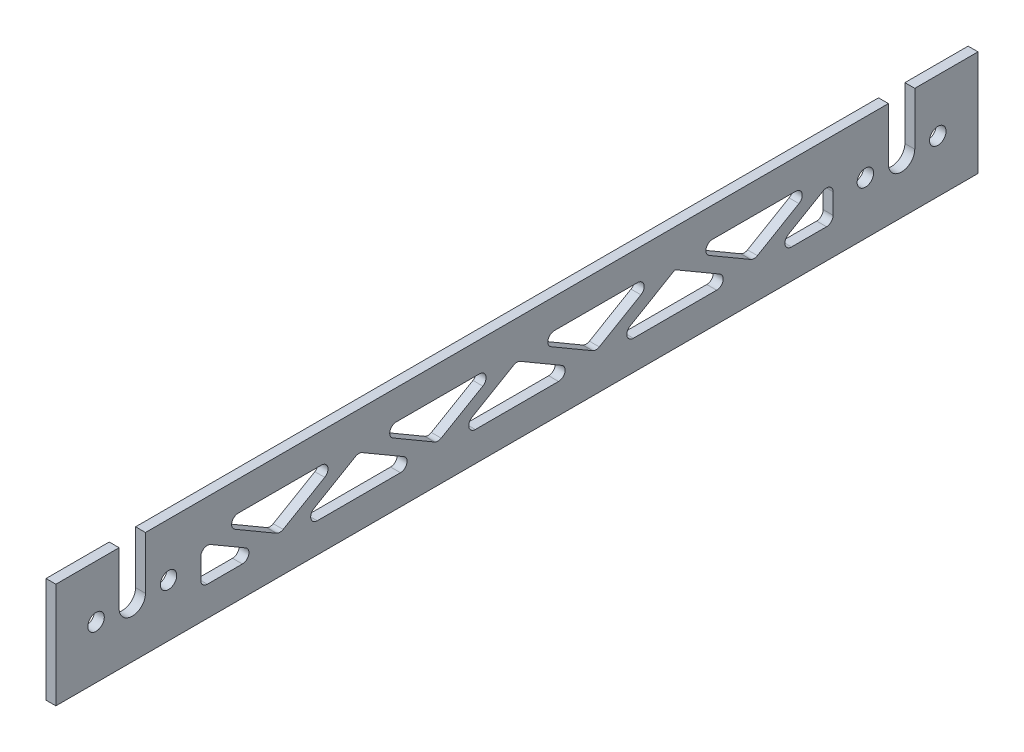
SolidWorks part; units mm, degrees
material "Thornel Mat VMA"
ref_plane "Front Plane" through (0, 0, 0) normal (0, 0, 1) x (1, 0, 0)
ref_plane "Top Plane" through (0, 0, 0) normal (0, 1, 0) x (1, 0, 0)
ref_plane "Right Plane" through (0, 0, 0) normal (1, 0, 0) x (0, 0, -1)
sketch "Sketch1" plane through (0, 0, 0) normal (1, 0, 0) x (0, 0, -1)
  line L0 (0, 0) -> (0, 75.5)
  line L2 (21.5, 75.5) -> (40, 0)
  line L3 (40, 0) -> (35.8817, 0)
  line L4 (35.8817, 0) -> (29.7558, 25)
  line L5 (29.7558, 25) -> (4, 25)
  line L6 (4, 25) -> (4, 0)
  line L7 (4, 0) -> (0, 0)
  line L8 (4, 69.5) -> (18.8519, 69.5)
  line L9 (18.8519, 69.5) -> (4, 29)
  line L10 (4, 29) -> (4, 69.5)
  line L11 (8.2605, 29) -> (20.5584, 62.5355)
  line L12 (20.5584, 62.5355) -> (28.7757, 29)
  line L13 (28.7757, 29) -> (8.2605, 29)
  line L15 (21.5, 75.5) -> (0, 75.5)
  circle A0 centre (5.5, 72.5) radius 1.05
  circle A1 centre (18.5, 72.5) radius 1.05
  dimension "D4" = 2.1
  dimension "D1" = 4
  dimension "D2" = 4
  dimension "D3" = 25
  dimension "D5" = 72.5
  dimension "D6" = 40
  dimension "D8" = 13
  dimension "D9" = 5.5
  dimension "D10" = 3
  dimension "D11" = 4
  dimension "D12" = 3
  dimension "D13" = 4
  dimension "D7" = 3
extrude "Boss-Extrude1" add sketch "Sketch1" along normal blind 1.5
fillet "Fillet1" radius 1.5 9 edges at (0.75, 29, -4) (0.75, 29, -8.2605) (0.75, 25, -29.7558) (0.75, 25, -4) (0.75, 69.5, -4) (0.75, 69.5, -18.8519) (0.75, 62.5355, -20.5584) (0.75, 29, -28.7757) (0.75, 75.5, -21.5)
sketch "Sketch2" plane through (1.5, 0, 0) normal (1, 0, 0) x (0, 0, -1)
  line L0 (70, 16) -> (70, 0) construction
  line L3 (0, 16) -> (103.9205, 16)
  line L14 (109.9641, 23.857) -> (108.0389, 16)
  line L15 (134.5, 25) -> (111.421, 25)
  line L16 (136, 16) -> (136, 23.5)
  line L18 (140, 75.5) -> (140, 0)
  line L19 (119.6768, 75.5) -> (140, 75.5)
  line L20 (103.9205, 16) -> (118.2199, 74.357)
  line L37 (140, 0) -> (140, 16)
  line L195 (108.0389, 16) -> (136, 16)
  line L197 (0, 16) -> (0, 0)
  line L208 (140, 0) -> (0, 0)
  line L212 (129.5918, 29) -> (113.1362, 29)
  line L215 (121.1357, 57.9158) -> (131.0001, 31.0164)
  line L216 (111.6793, 30.857) -> (118.2705, 57.7563)
  line L217 (123.2959, 69.5) -> (134.5, 69.5)
  line L218 (136, 68) -> (136, 37.4472)
  line L219 (133.0917, 36.9307) -> (121.8876, 67.4836)
  arc A3 (109.9641, 23.857) -> (111.421, 25) centre (111.421, 23.5) cw
  arc A4 (134.5, 25) -> (136, 23.5) centre (134.5, 23.5) cw
  arc A5 (118.2199, 74.357) -> (119.6768, 75.5) centre (119.6768, 74) cw
  arc A261 (131.0001, 31.0164) -> (129.5918, 29) centre (129.5918, 30.5) cw
  arc A268 (118.2705, 57.7563) -> (121.1357, 57.9158) centre (119.7274, 57.3993) cw
  arc A269 (113.1362, 29) -> (111.6793, 30.857) centre (113.1362, 30.5) cw
  arc A270 (134.5, 69.5) -> (136, 68) centre (134.5, 68) cw
  arc A271 (121.8876, 67.4836) -> (123.2959, 69.5) centre (123.2959, 68) cw
  arc A272 (136, 37.4472) -> (133.0917, 36.9307) centre (134.5, 37.4472) cw
  circle A273 centre (121.5, 72.5) radius 1.05
  circle A274 centre (134.5, 72.5) radius 1.05
  line M36 (40, 0) -> (21.7801, 74.357)
  line M39 (0, 75.5) -> (0, 0)
  line M40 (0, 0) -> (4, 0)
  line M41 (4, 0) -> (4, 23.5)
  line M45 (30.0359, 23.857) -> (35.8817, 0)
  line M46 (35.8817, 0) -> (40, 0)
extrude "Boss-Extrude2" add sketch "Sketch2" against normal up to surface (1.5 mm away) contours L0 L3 L208 M36 | L3 L0 L208 L18 L19 A5 L20 A273 L15 A4 L16 L195 L14 A3 L212 A269 L216 A268 L215 A261 L218 A272 L219 A271 L217 A270 A274 | L208 L3 M45 M41 | L3 M45 M46 M36 | L3 M39 M40 M41 up to face at (0, 72.5, -6.55)
sketch "Sketch4" plane through (1.5, 0, 0) normal (1, 0, 0) x (0, 0, -1)
  line L0 (70, 16) -> (70, 0) construction
  line L1 (36.0795, 16) -> (103.9205, 16) construction
  line L2 (0, 0) -> (140, 0) construction
  line L3 (6.1, 8) -> (11.6, 8) construction
  line L4 (11.6, 8) -> (17.1, 8) construction
  line L5 (0, 75.5) -> (0, 0) construction
  line L12 (126.4, 16) -> (130.4, 16)
  line L13 (130.4, 16) -> (130.4, 8)
  line L14 (126.4, 8) -> (126.4, 16)
  line L15 (9.6, 16) -> (13.6, 16)
  line L16 (13.6, 16) -> (13.6, 8)
  line L17 (9.6, 8) -> (9.6, 16)
  circle A0 centre (6.1, 8) radius 1.25
  circle A1 centre (17.1, 8) radius 1.25
  circle A3 centre (122.9, 8) radius 1.25
  circle A5 centre (133.9, 8) radius 1.25
  arc A6 (126.4, 8) -> (130.4, 8) centre (128.4, 8) ccw
  arc A7 (13.6, 8) -> (9.6, 8) centre (11.6, 8) cw
  dimension "D1" = 6.1
  dimension "D3" = 2.5
  dimension "D4" = 11
  dimension "D5" = 8
extrude "Cut-Extrude2" cut sketch "Sketch4" against normal through all
sketch "Sketch5" plane through (1.5, 0, 0) normal (1, 0, 0) x (0, 0, -1)
  line L0 (35.9846, 4.5) -> (46, 4.5)
  line L5 (47.9846, 11.5) -> (68.0154, 11.5)
  line L6 (59.9846, 4.5) -> (70, 4.5)
  line L17 (22, 4.5) -> (22, 10.3423)
  line L18 (23.9846, 11.5) -> (44.0154, 11.5)
  line L19 (118, 4.5) -> (118, 10.3423)
  line L21 (22, 4.5) -> (32.0154, 4.5)
  line L22 (46, 4.5) -> (56.0154, 4.5)
  line L24 (70, 4.5) -> (80.0154, 4.5)
  line L25 (94, 4.5) -> (104.0154, 4.5)
  line L26 (107.9846, 4.5) -> (118, 10.3423)
  line L27 (107.9846, 4.5) -> (118, 4.5)
  line L28 (83.9846, 4.5) -> (94, 4.5)
  line L29 (95.9846, 11.5) -> (116.0154, 11.5)
  line L30 (71.9846, 11.5) -> (92.0154, 11.5)
  line L34 (32.0154, 4.5) -> (22, 10.3423)
  line L35 (35.9846, 4.5) -> (46, 10.3423)
  line L36 (46, 10.3423) -> (56.0154, 4.5)
  line L37 (59.9846, 4.5) -> (70, 10.3423)
  line L38 (70, 10.3423) -> (80.0154, 4.5)
  line L39 (83.9846, 4.5) -> (94, 10.3423)
  line L40 (94, 10.3423) -> (104.0154, 4.5)
  line L42 (34, 5.6577) -> (23.9846, 11.5)
  line L43 (34, 5.6577) -> (44.0154, 11.5)
  line L44 (47.9846, 11.5) -> (58, 5.6577)
  line L45 (58, 5.6577) -> (68.0154, 11.5)
  line L46 (71.9846, 11.5) -> (82, 5.6577)
  line L47 (82, 5.6577) -> (92.0154, 11.5)
  line L48 (95.9846, 11.5) -> (106, 5.6577)
  line L49 (106, 5.6577) -> (116.0154, 11.5)
  point P4 (46, 4.5)
  point P6 (22, 4.5)
  point P7 (118, 11.5)
  point P8 (94, 4.5)
  point P10 (70, 4.5)
extrude "Cut-Extrude4" cut sketch "Sketch5" against normal through all
fillet "Fillet3" radius 1 26 edges at (0.75, 11.5, -95.9846) (0.75, 11.5, -116.0154) (0.75, 10.3423, -118) (0.75, 4.5, -107.9846) (0.75, 4.5, -118) (0.75, 4.5, -104.0154) (0.75, 4.5, -83.9846) (0.75, 11.5, -92.0154) (0.75, 11.5, -71.9846) (0.75, 5.6577, -106) (0.75, 5.6577, -82) (0.75, 4.5, -80.0154) (0.75, 4.5, -59.9846) (0.75, 10.3423, -70) (0.75, 11.5, -68.0154) (0.75, 11.5, -47.9846) (0.75, 5.6577, -58) (0.75, 4.5, -56.0154) (0.75, 10.3423, -46) (0.75, 4.5, -35.9846) (0.75, 5.6577, -34) (0.75, 11.5, -44.0154) (0.75, 4.5, -32.0154) (0.75, 4.5, -22) (0.75, 10.3423, -22) (0.75, 11.5, -23.9846)
fillet "Fillet4" radius 1.5 6 edges at (0.75, 16, -136) (0.75, 16, -108.0389) (0.75, 16, -103.9205) (0.75, 16, -31.9611) (0.75, 16, -36.0795) (0.75, 16, -4)
sketch "Sketch6" plane through (1.5, 0, 0) normal (1, 0, 0) x (0, 0, -1)
  line L0 (0, 75.5) -> (0, 0) construction
  line L1 (0, 16) -> (140, 16)
  line L2 (0, 16) -> (0, 75.5)
  line L3 (0, 75.5) -> (140, 75.5)
  line L4 (140, 16) -> (140, 75.5)
extrude "Cut-Extrude5" cut sketch "Sketch6" against normal blind 10
sketch "Sketch3" plane through (1.5, 0, 0) normal (1, 0, 0) x (0, 0, -1)
  line L0 (70, 16) -> (70, 0) construction
  line L1 (0, 0) -> (8, 0)
  line L2 (0, 0) -> (0, 8)
  line L3 (0, 8) -> (8, 8)
  line L4 (8, 0) -> (8, 8)
  line L5 (36.0795, 16) -> (103.9205, 16) construction
  line L6 (0, 0) -> (140, 0) construction
  line L7 (140, 8) -> (132, 8)
  line L8 (132, 0) -> (132, 8)
  line L9 (140, 0) -> (132, 0)
  line L10 (140, 0) -> (140, 8)
  dimension "D1" = 8
equation "\"D2@Sketch1\"=\"D1@Sketch1\""
equation "\"D10@Sketch1\"=\"D7@Sketch1\""
equation "\"D11@Sketch1\"=\"D1@Sketch1\""
equation "\"D12@Sketch1\"=\"D7@Sketch1\""
equation "\"D13@Sketch1\"=\"D1@Sketch1\""
